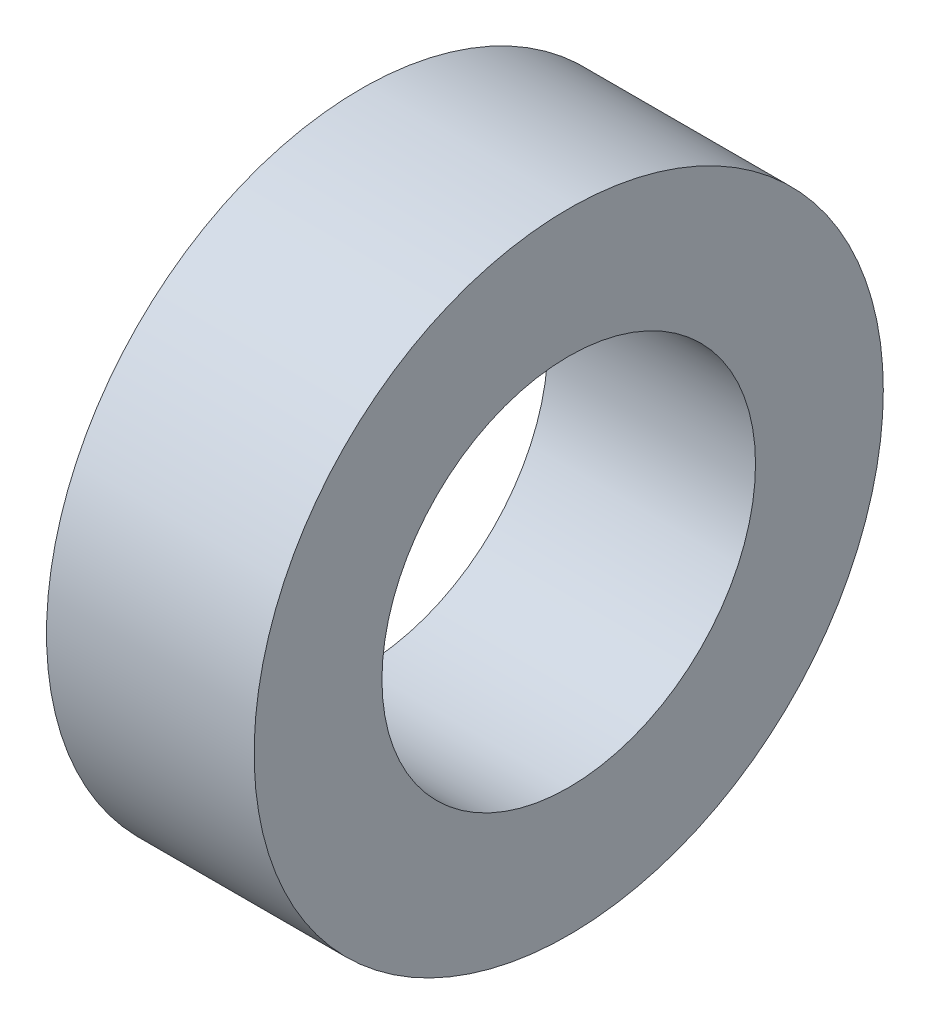
SolidWorks part; units mm, degrees
material "Nylon 101"
ref_plane "Front Plane" through (0, 0, 0) normal (0, 0, 1) x (1, 0, 0)
ref_plane "Top Plane" through (0, 0, 0) normal (0, 1, 0) x (1, 0, 0)
ref_plane "Right Plane" through (0, 0, 0) normal (1, 0, 0) x (0, 0, -1)
sketch "Sketch1" plane through (0, 0, 0) normal (1, 0, 0) x (0, 0, -1)
  line L1 (-7.3323, 0) -> (-3.6662, -6.35) construction
  line L2 (-3.6662, -6.35) -> (3.6662, -6.35) construction
  line L3 (3.6662, -6.35) -> (7.3323, 0) construction
  line L4 (7.3323, 0) -> (3.6662, 6.35) construction
  line L5 (3.6662, 6.35) -> (-3.6662, 6.35) construction
  line L6 (-3.6662, 6.35) -> (-7.3323, 0) construction
  circle A0 centre (0, 0) radius 7.5406
  circle A1 centre (0, 0) radius 12.7
  circle A2 centre (0, 0) radius 6.35 construction
  dimension "D1" = 25.4
  dimension "D2" = 12.7
  dimension "D3" = 15.0812
extrude "Boss-Extrude1" add sketch "Sketch1" along normal blind 8.382
